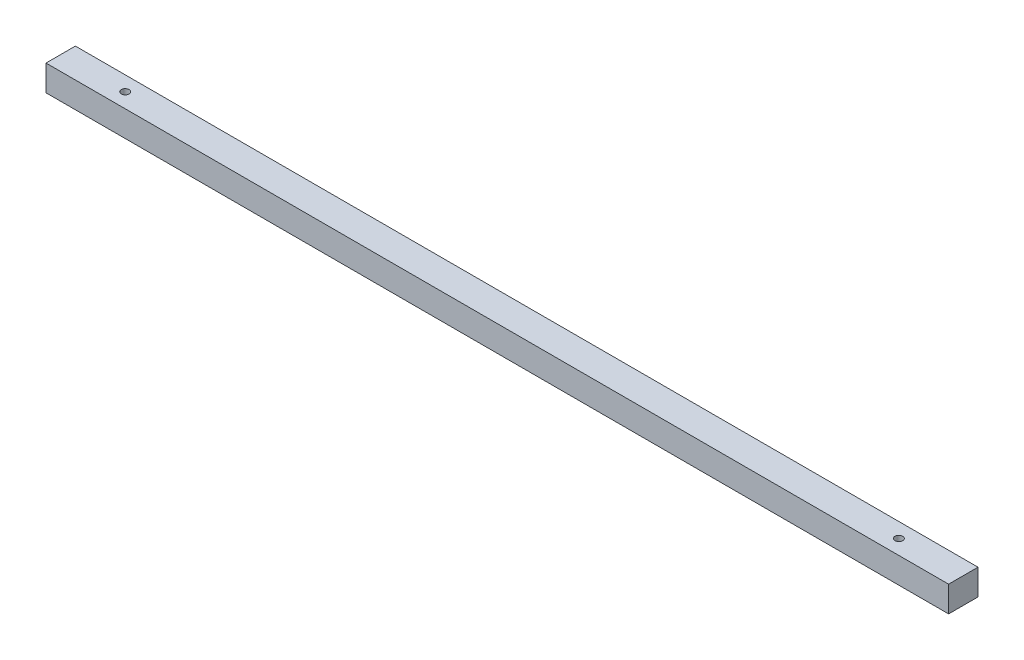
SolidWorks part; units mm, degrees
ref_plane "前视基准面" through (0, 0, 0) normal (0, 0, 1) x (1, 0, 0)
ref_plane "上视基准面" through (0, 0, 0) normal (0, 1, 0) x (1, 0, 0)
ref_plane "右视基准面" through (0, 0, 0) normal (1, 0, 0) x (0, 0, -1)
other "Configuration Table"
sketch "草图1" plane through (0, 0, 0) normal (0, 1, 0) x (1, 0, 0)
  line L0 (-150, 0) -> (150, 0)
  line L1 (-175, -5.7) -> (175, -5.7)
  line L2 (-175, -5.7) -> (-175, 5.7)
  line L3 (-175, 5.7) -> (175, 5.7)
  line L4 (175, -5.7) -> (175, 5.7)
  line L5 (-175, -5.7) -> (175, 5.7) construction
  line L6 (-175, 5.7) -> (175, -5.7) construction
  circle A0 centre (-150, 0) radius 1.5
  circle A1 centre (150, 0) radius 1.5
  point P0 (0, 0)
  point P6 (0, 0)
  point P7 (0, 0)
  point P12 (0, 0)
  point P13 (0, 0)
  dimension "D3" = 3
  dimension "D1" = 350
  dimension "D2" = 11.4
  dimension "D4" = 300
extrude "凸台-拉伸1" add sketch "草图1" along normal blind 10 contours L1 L4 L3 L2 | A0 | A1
